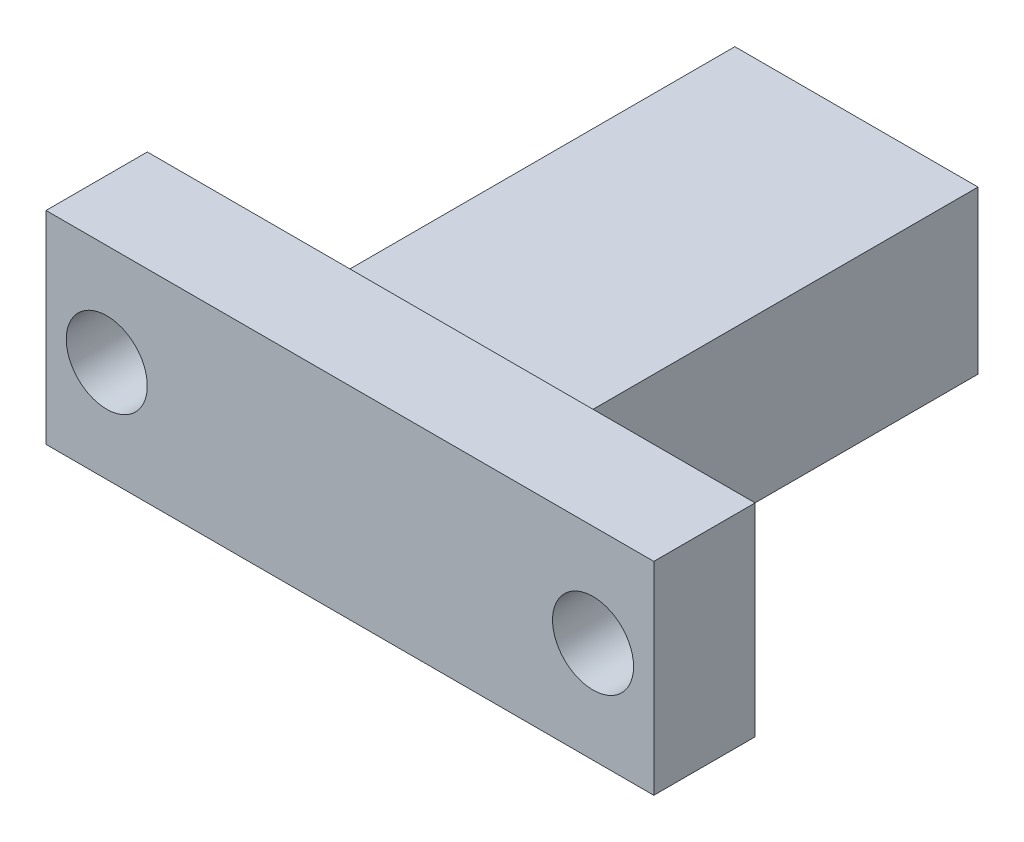
SolidWorks part; units mm, degrees
material "ABS"
ref_plane "Front" through (0, 0, 0) normal (0, 0, 1) x (1, 0, 0)
ref_plane "Top" through (0, 0, 0) normal (0, 1, 0) x (1, 0, 0)
ref_plane "Right" through (0, 0, 0) normal (1, 0, 0) x (0, 0, -1)
sketch "Sketch1" plane through (0, 0, 0) normal (0, 0, 1) x (1, 0, 0)
  line L0 (0, 21.3333) -> (0, -21.3333) construction
  line L2 (-15, -5) -> (15, -5)
  line L3 (-15, -5) -> (-15, 5)
  line L4 (-15, 5) -> (15, 5)
  line L5 (15, -5) -> (15, 5)
  line L6 (-15, -5) -> (15, 5) construction
  line L7 (-15, 5) -> (15, -5) construction
  circle A0 centre (12, 0) radius 2
  circle A1 centre (-12, 0) radius 2
  point P4 (0, 0)
  point P7 (0, 0)
  dimension "D1" = 4
  dimension "D2" = 12
  dimension "D3" = 10
  dimension "D4" = 3
extrude "Boss-Extrude1" add sketch "Sketch1" along normal blind 5
sketch "Sketch2" plane through (0, 0, 0) normal (0, 0, -1) x (-1, 0, 0)
  line L1 (-6, -4) -> (6, -4)
  line L2 (-6, -4) -> (-6, 4)
  line L3 (-6, 4) -> (6, 4)
  line L4 (6, -4) -> (6, 4)
  line L5 (-6, -4) -> (6, 4) construction
  line L6 (-6, 4) -> (6, -4) construction
  point P0 (0, 0)
  dimension "D1" = 8
  dimension "D2" = 12
  dimension "D3" = 33.69
extrude "Boss-Extrude2" add sketch "Sketch2" along normal blind 20
ref_plane "Plane1" through (-5, -5, 0) normal (-0.7071, -0.7071, 0) x (-0.7071, 0.7071, 0)
sketch "Sketch3" plane through (-5, -5, 0) normal (-0.7071, -0.7071, 0) x (-0.7071, 0.7071, 0)
  line L0 (1.4142, 20) -> (1.4142, 0) construction
  line L1 (7.0711, 0) -> (-14.1421, 0) construction
  circle A0 centre (1.4142, 10) radius 5
  dimension "D1" = 10
  dimension "D2" = 10
extrude "Cut-Extrude1" cut sketch "Sketch3" against normal blind 6
